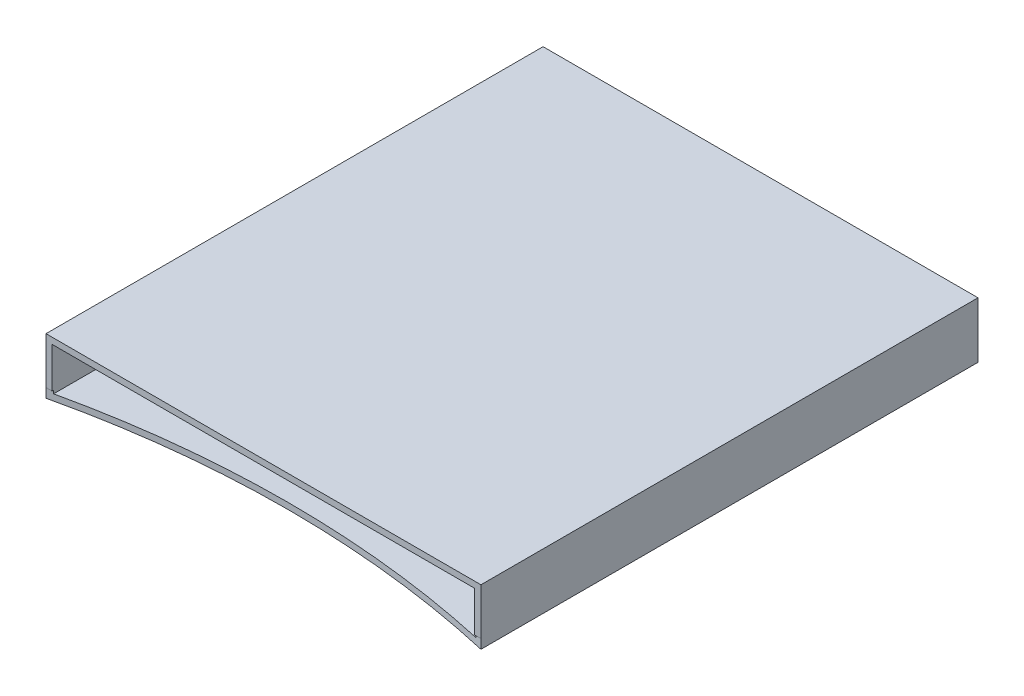
SolidWorks part; units mm, degrees
ref_plane "前视基准面" through (0, 0, 0) normal (0, 0, 1) x (1, 0, 0)
ref_plane "上视基准面" through (0, 0, 0) normal (0, 1, 0) x (1, 0, 0)
ref_plane "右视基准面" through (0, 0, 0) normal (1, 0, 0) x (0, 0, -1)
sketch "草图1" plane through (0, 0, 0) normal (0, 1, 0) x (1, 0, 0)
  line L0 (-42.7555, 0) -> (52.7621, 0) construction
  line L1 (-7, 8) -> (7, 8)
  line L2 (-7, 8) -> (-7, -8)
  line L3 (-7, -8) -> (7, -8)
  line L4 (7, 8) -> (7, -8)
  line L5 (0, 37.6006) -> (0, -33.9618) construction
  dimension "D1" = 14
  dimension "D2" = 16
extrude "拉伸1" add sketch "草图1" along normal blind 1.8
shell "抽壳1" thickness 0.2
sketch "草图2" plane through (0, 0, 0) normal (0, -1, 0) x (1, 0, 0)
  line L0 (0, 9.8052) -> (0, -10.1985) construction
  line L1 (7, 8) -> (-7, 8)
  arc A0 (7, 8) -> (-7, 8) centre (0, 38.522) cw
extrude "切除-拉伸2" cut sketch "草图2" against normal blind 0.3
